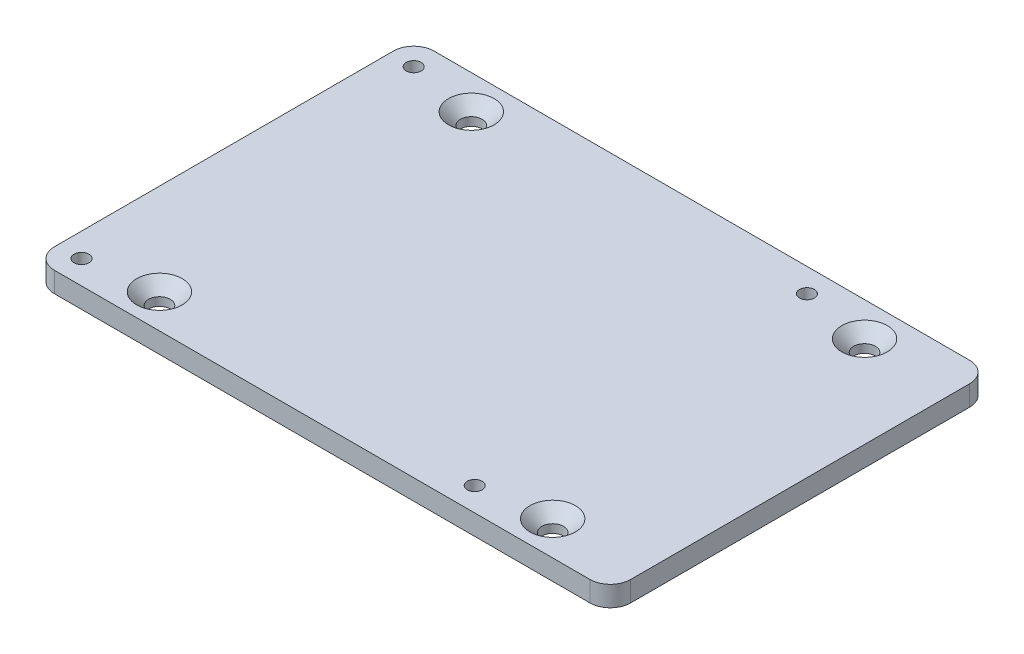
SolidWorks part; units mm, degrees
material "6061-T6 (SS)"
ref_plane "Front Plane" through (0, 0, 0) normal (0, 0, 1) x (1, 0, 0)
ref_plane "Top Plane" through (0, 0, 0) normal (0, 1, 0) x (1, 0, 0)
ref_plane "Right Plane" through (0, 0, 0) normal (1, 0, 0) x (0, 0, -1)
sketch "Sketch1" plane through (0, 0, 0) normal (0, 1, 0) x (1, 0, 0)
  line L1 (42.5, -28) -> (-42.5, -28)
  line L2 (42.5, -28) -> (42.5, 28)
  line L3 (42.5, 28) -> (-42.5, 28)
  line L4 (-42.5, -28) -> (-42.5, 28)
  line L5 (42.5, -28) -> (-42.5, 28) construction
  line L6 (42.5, 28) -> (-42.5, -28) construction
  point P0 (0, 0)
  dimension "D1" = 85
  dimension "D2" = 56
extrude "Boss-Extrude1" add sketch "Sketch1" along normal blind 3
hole_wizard "M2 Clearance Hole1" positions "Sketch2" profile "Sketch3" hole size "M2" standard "ANSI Metric"
sketch "Sketch2" plane through (0, 3, 0) normal (0, 1, 0) x (1, 0, 0)
  line L1 (19, -24.5) -> (-39, -24.5)
  line L2 (19, -24.5) -> (19, 24.5)
  line L3 (19, 24.5) -> (-39, 24.5)
  line L4 (-39, -24.5) -> (-39, 24.5)
  line L5 (19, -24.5) -> (-39, 24.5) construction
  line L6 (19, 24.5) -> (-39, -24.5) construction
  line L7 (-42.5, 28) -> (-42.5, -28) construction
  point P2 (-39, 24.5)
  point P67 (19, -24.5)
  point P68 (19, 24.5)
  point P69 (-39, -24.5)
  point P72 (-10, 0)
  dimension "D1" = 58
  dimension "D2" = 49
  dimension "D3" = 3.5
sketch "Sketch3" plane through (-39, 3, -24.5) normal (1, 0, 0) x (0, 0, 1)
  line L0 (0, 0) -> (0, 5.6609)
  line L1 (0, 5.6609) -> (1.1, 5)
  line L2 (1.1, 5) -> (1.1, 0)
  line L5 (1.1, 0) -> (0, 0)
  line L10 (0, 5.6609) -> (-1.1, 5) construction
  line L11 (0, -6.35) -> (0, 107.95) construction
  dimension "Hole Dia." = 2.2
  dimension "Hole Depth" = 5
  dimension "Drill Angle" = 118
fillet "Fillet1" radius 3 4 edges at (42.5, 1.5, -28) (42.5, 1.5, 28) (-42.5, 1.5, 28) (-42.5, 1.5, -28)
hole_wizard "CSK for M3 SFHCS1" positions "Sketch4" profile "Sketch6" countersink size "M3" standard "ANSI Metric" end condition through all
sketch "Sketch4" plane through (0, 3, 0) normal (0, -1, 0) x (-1, 0, 0)
  line L1 (29, 23) -> (-29, 23)
  line L2 (29, 23) -> (29, -23)
  line L3 (29, -23) -> (-29, -23)
  line L4 (-29, 23) -> (-29, -23)
  line L5 (-42.5, -25) -> (-42.5, 25) construction
  circle A0 centre (39, 24.5) radius 1.1 construction
  point P1 (29, 23)
  point P2 (-29, -23)
  point P73 (29, -23)
  point P74 (-29, 23)
  point P76 (29, 0)
  dimension "D1" = 10
  dimension "D2" = 46
  dimension "D3" = 13.5
sketch "Sketch6" plane through (-29, 3, -23) normal (1, 0, 0) x (0, 0, 1)
  line L0 (0, 0) -> (0, 3)
  line L1 (0, 3) -> (1.6, 3)
  line L2 (1.6, 3) -> (1.6, 1.76)
  line L3 (1.6, 1.76) -> (3.36, 0)
  line L5 (3.36, 0) -> (0, 0)
  line L6 (-1.6, 1.76) -> (-3.36, 0) construction
  line L11 (0, -6.35) -> (0, 107.95) construction
  dimension "Thru Hole Dia." = 3.2
  dimension "Thru Hole Depth" = 3
  dimension "Near C'Sink Dia." = 6.72
  dimension "Near C'Sink Angle" = 90
